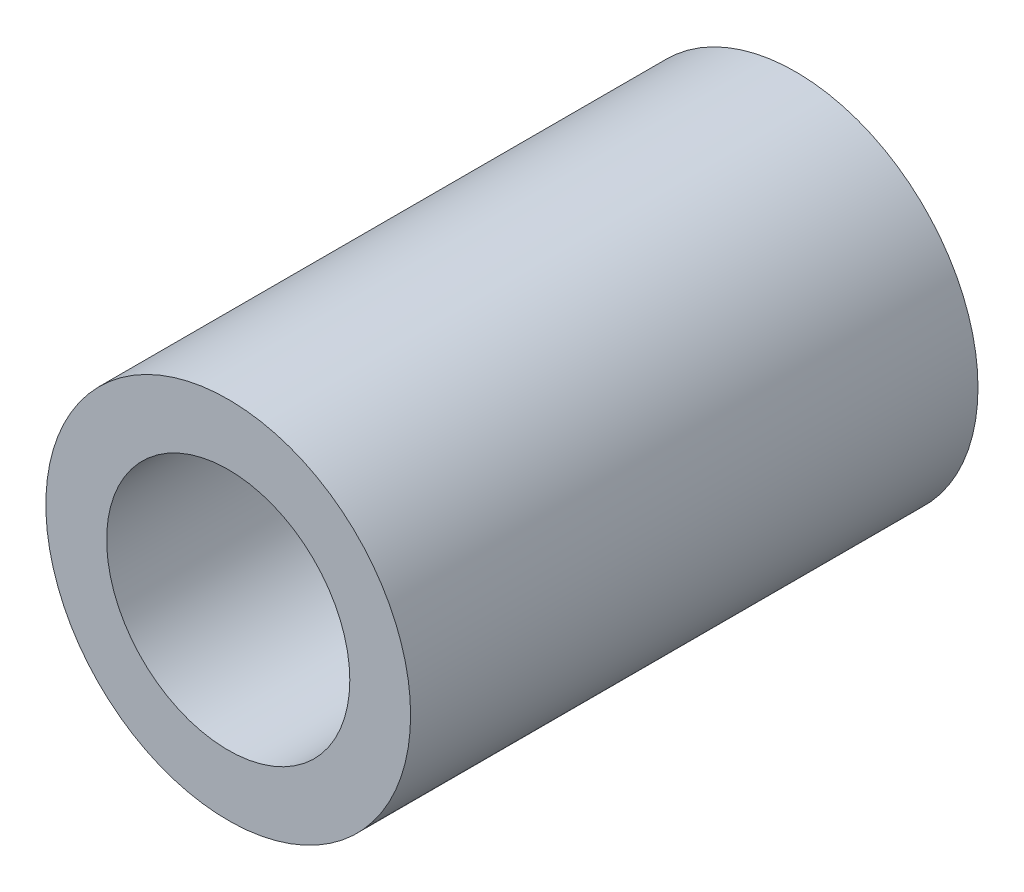
SolidWorks part; units mm, degrees
ref_plane "Front Plane" through (0, 0, 0) normal (0, 0, 1) x (1, 0, 0)
ref_plane "Top Plane" through (0, 0, 0) normal (0, 1, 0) x (1, 0, 0)
ref_plane "Right Plane" through (0, 0, 0) normal (1, 0, 0) x (0, 0, -1)
sketch "Sketch1" plane through (0, 0, 0) normal (0, 0, 1) x (1, 0, 0)
  circle A0 centre (0, 0) radius 2.25
  circle A1 centre (0, 0) radius 1.5
  dimension "D1" = 3
  dimension "D2" = 4.5
extrude "Boss-Extrude1" add sketch "Sketch1" along normal blind 7
